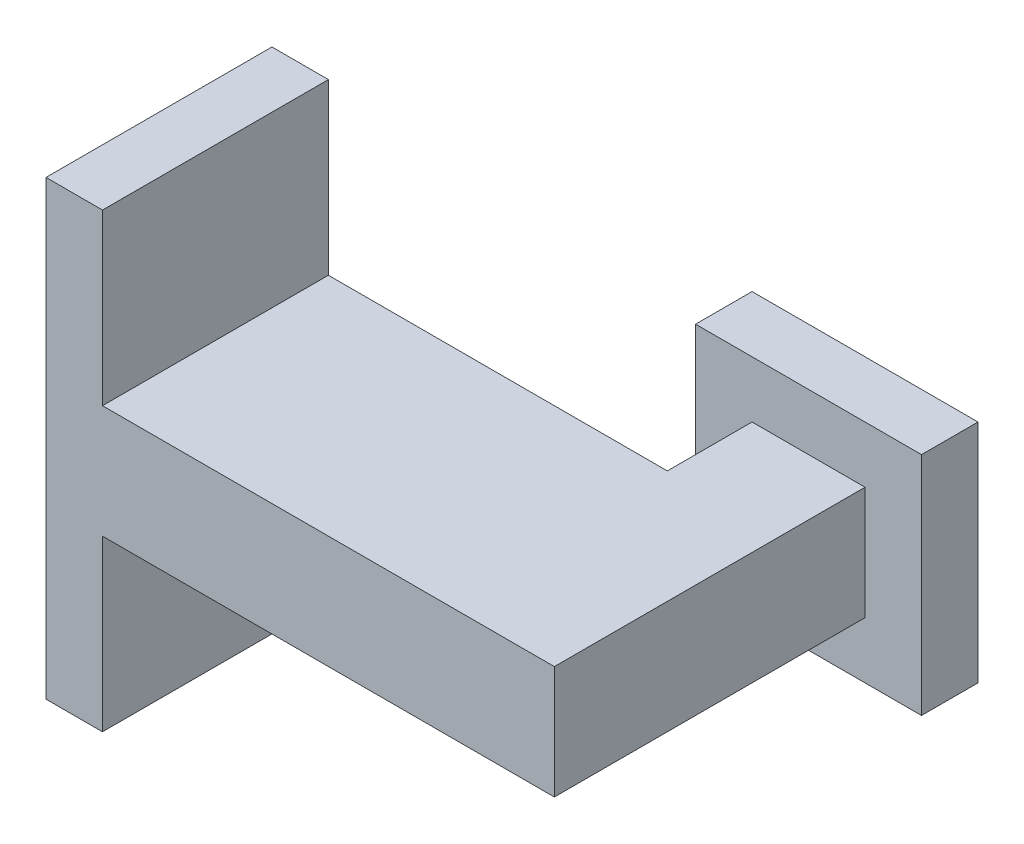
SolidWorks part; units mm, degrees
ref_plane "Plan de face" through (0, 0, 0) normal (0, 0, 1) x (1, 0, 0)
ref_plane "Plan de dessus" through (0, 0, 0) normal (0, 1, 0) x (1, 0, 0)
ref_plane "Plan de droite" through (0, 0, 0) normal (1, 0, 0) x (0, 0, -1)
sketch "Esquisse1" plane through (0, 0, 0) normal (0, 0, 1) x (1, 0, 0)
  line L1 (-10, 10) -> (10, 10)
  line L2 (-10, 10) -> (-10, -10)
  line L3 (-10, -10) -> (10, -10)
  line L4 (10, 10) -> (10, -10)
  dimension "D1" = 20
  dimension "D2" = 20
  dimension "D3" = 10
  dimension "D4" = 10
extrude "Boss.-Extru.1" add sketch "Esquisse1" along normal blind 5
sketch "Esquisse3" plane through (0, 0, 5) normal (0, 0, 1) x (1, 0, 0)
  line L1 (-5, 5) -> (5, 5)
  line L2 (-5, 5) -> (-5, -5)
  line L3 (-5, -5) -> (5, -5)
  line L4 (5, 5) -> (5, -5)
  dimension "D1" = 10
  dimension "D2" = 10
  dimension "D3" = 5
  dimension "D4" = 5
extrude "Boss.-Extru.2" add sketch "Esquisse3" along normal blind 27.5
sketch "Esquisse7" plane through (-5, 0, 0) normal (-1, 0, 0) x (0, 0, 1)
  line L0 (32.5, 5) -> (5, 5) construction
  line L1 (12.5, 5) -> (32.5, 5)
  line L2 (12.5, 5) -> (12.5, -5)
  line L3 (12.5, -5) -> (32.5, -5)
  line L4 (32.5, 5) -> (32.5, -5)
  dimension "D1" = 20
extrude "Boss.-Extru.3" add sketch "Esquisse7" along normal blind 30
sketch "Esquisse8" plane through (-35, 0, 0) normal (-1, 0, 0) x (0, 0, 1)
  line L0 (32.5, 5) -> (12.5, 5) construction
  line L1 (12.5, 20) -> (32.5, 20)
  line L2 (12.5, 20) -> (12.5, -20)
  line L3 (12.5, -20) -> (32.5, -20)
  line L4 (32.5, 20) -> (32.5, -20)
  line L5 (12.5, -5) -> (32.5, -5) construction
  line L6 (32.5, -5) -> (32.5, 5) construction
  dimension "D1" = 40
  dimension "D2" = 15
extrude "Boss.-Extru.4" add sketch "Esquisse8" along normal blind 5
sketch "Esquisse9" plane through (0, 0, 0) normal (0, 0, -1) x (-1, 0, 0)
  circle A2 centre (0, 0) radius 1.5
  dimension "D1" = 3
extrude "Enlèv. mat.-Extru.1" cut sketch "Esquisse9" against normal blind 22
thread "Filetage1" pitch 0.3175 profile "Profil de filetage2" start angle 1, offset 1, length 15, pitch 1.25, diameter 3
ref_plane "Plan4" through (1.4998, 0.0262, 1) normal (0.0175, -0.9998, 0) x (0.9998, 0.0175, 0)
sketch "Profil de filetage2" plane through (1.4998, 0.0262, 1) normal (0.0175, -0.9998, 0) x (0.9998, 0.0175, 0)
  line L0 (0, 0) -> (0, 0.3175) construction
  line L1 (0, 0) -> (0.1719, 0.0992)
  line L2 (0.1719, 0.0992) -> (0.1719, 0.1389)
  line L3 (0.1719, 0.1389) -> (0, 0.2381)
  line L4 (0.1719, 0.1191) -> (0, 0.1191) construction
  line L11 (0, 0) -> (0, 0.2381)
  point P2 (0, 0)
  dimension "Pitch" = 0.3175
  dimension "Profile_Angle" = 60
  dimension "Profile_Land" = 0.0397
  dimension "Profile_Height" = 0.1719
